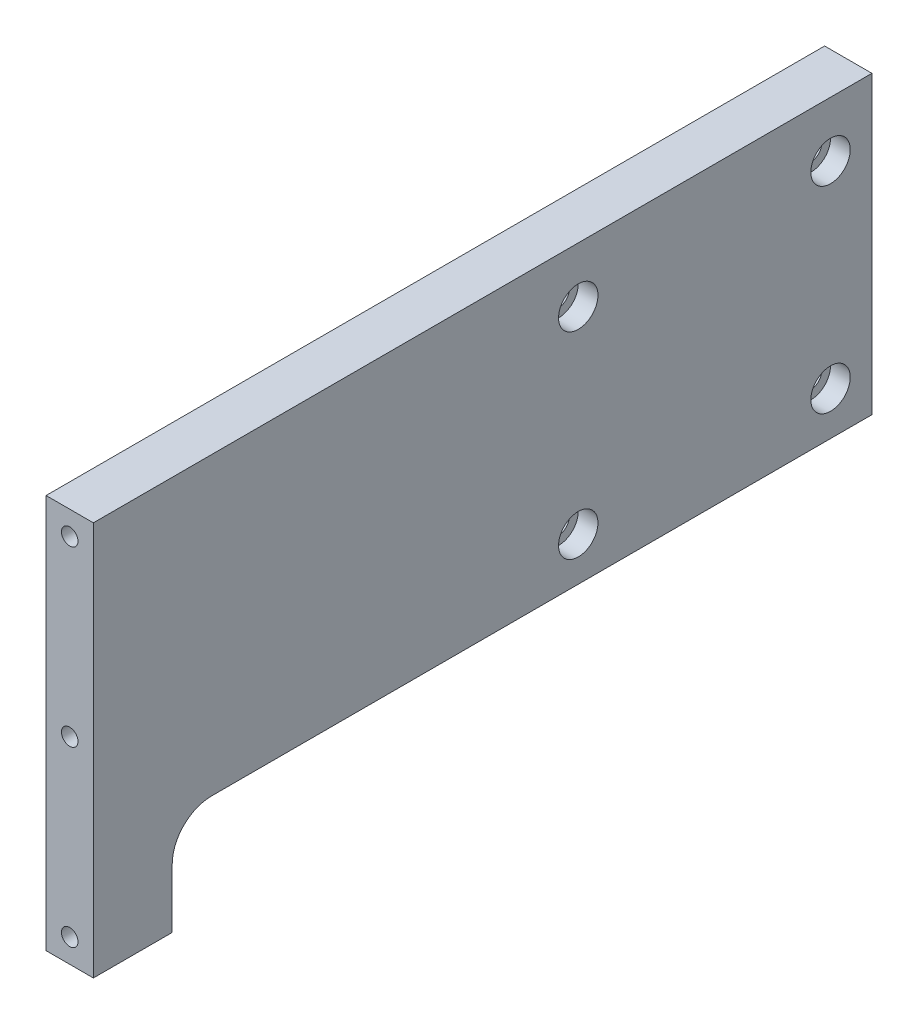
SolidWorks part; units mm, degrees
ref_plane "Front" through (0, 0, 0) normal (0, 0, 1) x (1, 0, 0)
ref_plane "Top" through (0, 0, 0) normal (0, 1, 0) x (1, 0, 0)
ref_plane "Right" through (0, 0, 0) normal (1, 0, 0) x (0, 0, -1)
sketch "Sketch1" plane through (0, 0, 0) normal (1, 0, 0) x (0, 0, -1)
  line L1 (0, 0) -> (197.5, 0)
  line L2 (0, 0) -> (0, -100)
  line L3 (0, -100) -> (20, -100)
  line L4 (197.5, 0) -> (197.5, -75)
  line L5 (197.5, -75) -> (20, -75)
  line L8 (20, -75) -> (20, -100)
  dimension "D1" = 75
  dimension "D2" = 20
  dimension "D3" = 100
  dimension "D4" = 197.5
extrude "Boss-Extrude1" add sketch "Sketch1" along normal blind 12
fillet "Fillet1" radius 10 1 edges at (6, -75, -20)
hole_wizard "M5x0.8 Tapped Hole1" positions "Sketch2" profile "Sketch3" tap size "M5x0.8" standard "JIS"
sketch "Sketch2" plane through (0, 0, 0) normal (0, 0, 1) x (1, 0, 0)
  line L0 (0, 0) -> (0, -100) construction
  line L1 (12, 0) -> (0, 0) construction
  line L2 (12, -100) -> (0, -100) construction
  point P0 (6, -6)
  point P1 (6, -50)
  point P3 (6, -94)
  dimension "D1" = 6
  dimension "D2" = 6
  dimension "D3" = 44
  dimension "D4" = 44
  dimension "D5" = 6
sketch "Sketch3" plane through (6, -6, 0) normal (1, 0, 0) x (0, -1, 0)
  line L0 (0, 0) -> (0, 15.2618)
  line L1 (0, 15.2618) -> (2.1, 14)
  line L2 (2.1, 14) -> (2.1, 0)
  line L5 (2.1, 0) -> (0, 0)
  line L10 (0, 15.2618) -> (-2.1, 14) construction
  line L11 (0, -6.35) -> (0, 107.95) construction
  dimension "ねじ下穴ﾄﾞﾘﾙ直径" = 4.2
  dimension "ねじ下穴ﾄﾞﾘﾙの深さ" = 14
  dimension "ﾄﾞﾘﾙ角度" = 118
cosmetic thread "Hole Thread1" parameters "D1"=10, "D2"=5
cosmetic thread "Hole Thread2" parameters "D1"=10, "D2"=5
cosmetic thread "Hole Thread3" parameters "D1"=10, "D2"=5
hole_wizard "CBORE for M5 Socket Head Cap Screw1" positions "Sketch4" profile "Sketch5" counterbore size "M5" standard "JIS" end condition through all
sketch "Sketch4" plane through (12, 0, 0) normal (1, 0, 0) x (0, 0, -1)
  line L0 (155, 14.0711) -> (155, -84.5924) construction
  line L2 (197.5, 0) -> (0, 0) construction
  line L3 (0, 0) -> (0, -100) construction
  point P0 (123, -14)
  point P1 (123, -64)
  point P3 (187, -64)
  point P5 (187, -14)
  dimension "D1" = 64
  dimension "D2" = 50
  dimension "D3" = 14
  dimension "D4" = 155
sketch "Sketch5" plane through (12, -14, -123) normal (0, 1, 0) x (0, 0, -1)
  line L0 (0, 0) -> (0, 12)
  line L1 (0, 12) -> (2.75, 12)
  line L3 (2.75, 12) -> (2.75, 5)
  line L4 (2.75, 5) -> (5, 5)
  line L5 (5, 5) -> (5, 0)
  line L7 (5, 0) -> (0, 0)
  line L11 (0, -6.35) -> (0, 107.95) construction
  dimension "通し穴の直径" = 5.5
  dimension "通し穴の深さ" = 12
  dimension "座ぐり穴の直径" = 10
  dimension "座ぐり穴の深さ" = 5
